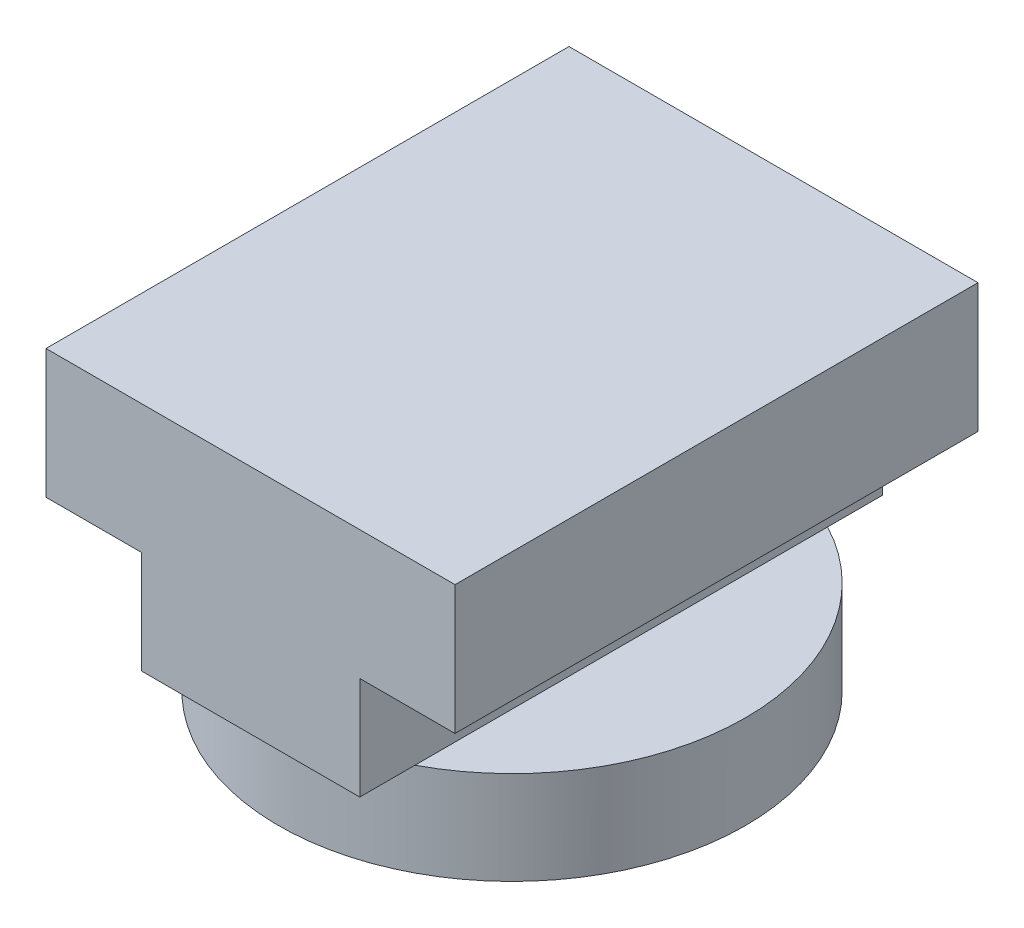
SolidWorks part; units mm, degrees
ref_plane "Спереди" through (0, 0, 0) normal (0, 0, 1) x (1, 0, 0)
ref_plane "Сверху" through (0, 0, 0) normal (0, 1, 0) x (1, 0, 0)
ref_plane "Справа" through (0, 0, 0) normal (1, 0, 0) x (0, 0, -1)
other "Configuration Table"
sketch "Sketch1" plane through (0, 0, 0) normal (0, 0, 1) x (1, 0, 0)
  line L0 (28.1483, 0) -> (5.85, 0) construction
  line L1 (0, -18.3368) -> (0, 18.3368) construction
  line L2 (-10.95, 0) -> (-5.85, 0)
  line L3 (10.95, 6.9) -> (-10.95, 6.9)
  line L4 (10.95, 6.9) -> (10.95, 0)
  line L5 (10.95, 0) -> (5.85, 0)
  line L6 (-10.95, 6.9) -> (-10.95, 0)
  line L7 (10.95, 6.9) -> (-10.95, 0) construction
  line L8 (10.95, 0) -> (-10.95, 6.9) construction
  line L9 (-5.85, 0) -> (-5.85, -5.5)
  line L10 (-5.85, -5.5) -> (5.85, -5.5)
  line L11 (5.85, 0) -> (5.85, -5.5)
  line L12 (-5.85, 0) -> (-28.1483, 0) construction
  line L13 (-5.85, 0) -> (-10.95, 0)
  point P0 (0, 3.45)
  point P4 (0, 0)
  point P8 (0, 0)
  point P17 (0, -5.5)
  dimension "D1" = 21.9
  dimension "D2" = 6.9
  dimension "D3" = 5.5
  dimension "D4" = 5.1
extrude "Boss-Extrude1" add sketch "Sketch1" against normal blind 28 contours L11 L5 L4 L3 L6 L2 L9 L10
sketch "Sketch3" plane through (0, -5.5, 0) normal (0, -1, 0) x (1, 0, 0)
  line L0 (-5.85, 0) -> (5.85, 0) construction
  circle A0 centre (0, -14) radius 12.5
  point P2 (0, -13.0499)
  point P3 (0, -13.752)
  dimension "D1" = 25
  dimension "D2" = 14
extrude "Boss-Extrude2" add sketch "Sketch3" along normal blind 5 contours A0
